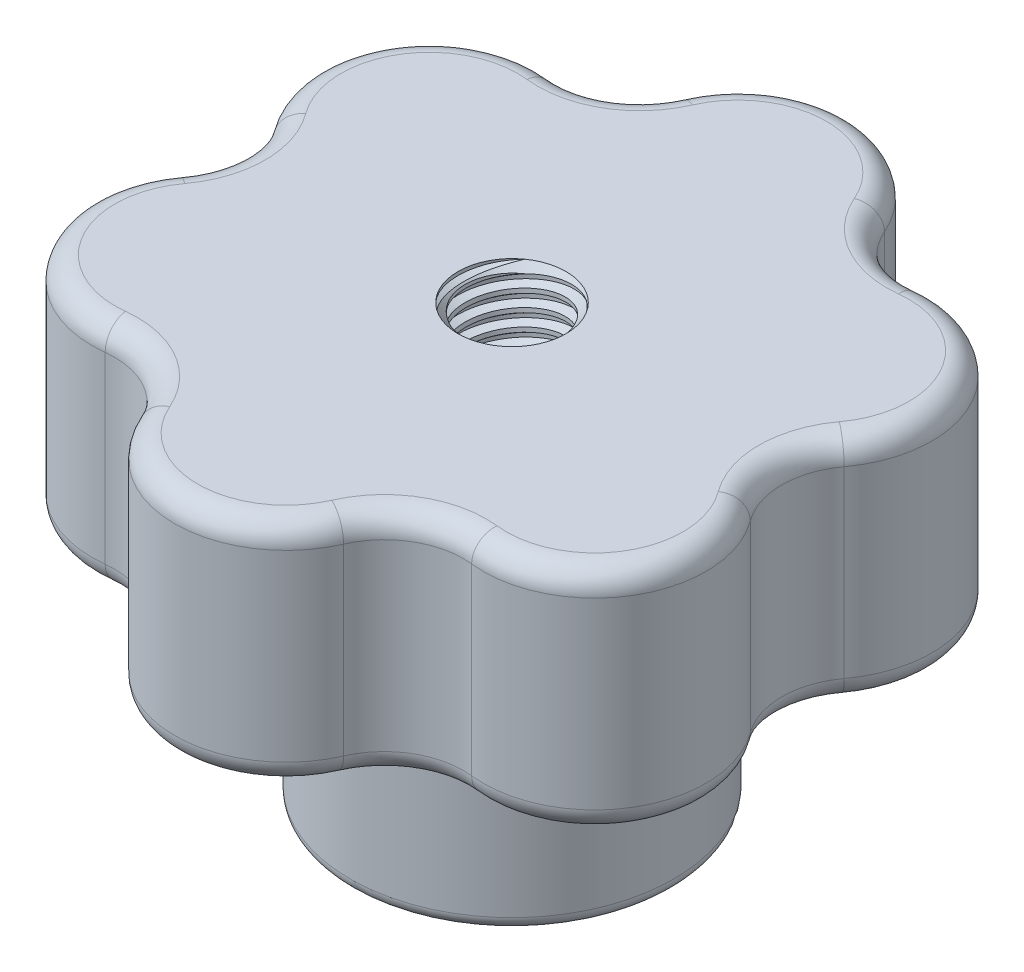
SolidWorks part; units mm, degrees
ref_plane "Front" through (0, 0, 0) normal (0, 0, 1) x (1, 0, 0)
ref_plane "Top" through (0, 0, 0) normal (0, 1, 0) x (1, 0, 0)
ref_plane "Right" through (0, 0, 0) normal (1, 0, 0) x (0, 0, -1)
sketch "Sketch1" plane through (0, 0, 0) normal (0, 0, 1) x (1, 0, 0)
  line L0 (0, 0) -> (12, 0)
  line L1 (12, 0) -> (12, 15)
  line L2 (12, 15) -> (25, 15)
  line L3 (25, 15) -> (25, 32)
  line L4 (0, 44.8994) -> (0, 32) construction
  line L5 (0, 0) -> (0, -12) construction
  line L7 (0, 0) -> (-12, 0) construction
  line L9 (0, 32) -> (25, 32)
  line L10 (0, 32) -> (0, 0)
  dimension "B Base Dia" = 24
  dimension "A OD" = 50
  dimension "F Base Height" = 15
  dimension "D5" = 90
  dimension "D6" = 0
  dimension "D1" = 17
  dimension "D2" = 32
revolve "Revolve1" add sketch "Sketch1" angle 360 about L5
ref_plane "Plane1" through (0, 15, 0) normal (0, 1, 0) x (-1, 0, 0)
sketch "Sketch11" plane through (0, 0, 0) normal (0, 1, 0) x (1, 0, 0)
  line L0 (0, 0) -> (21.6506, -12.5) construction
  line L1 (0, 0) -> (21.6506, 12.5) construction
  line L2 (-20, 0) -> (-25, 0) construction
  line L3 (21.6506, -12.5) -> (24.2487, -14)
  line L4 (21.6506, 12.5) -> (24.2487, 14)
  circle A0 centre (0, 0) radius 20 construction
  arc A1 (21.1438, 3.4759) -> (21.1438, -3.4759) centre (25.8534, 0) ccw
  arc A2 (21.1438, -3.4759) -> (21.6506, -12.5) centre (14.5059, -8.375) cw
  arc A3 (21.1438, 3.4759) -> (21.6506, 12.5) centre (14.5059, 8.375) ccw
  circle A5 centre (0, 0) radius 25 construction
  circle A6 centre (0, 0) radius 28
  arc A7 (24.2487, -14) -> (24.2487, 14) centre (0, 0) ccw
  dimension "D1" = 40
  dimension "D4" = 8.25
  dimension "D3" = 5
  dimension "D5" = 60
  dimension "D2" = 3
extrude "Cut-Extrude2" cut sketch "Sketch11" along normal through all
pattern_circular "CirPattern1" count 6 over 360 about axis through (0, 0, 0) along (0, 1, 0) of "Cut-Extrude2"
sketch "Sketch5" plane through (0, 0, 0) normal (0, 0, 1) x (1, 0, 0)
  line L0 (0, 0) -> (0, -12) construction
  line L1 (0, 0) -> (4, 0)
  line L2 (0, 0) -> (0, 32)
  line L3 (0, 32) -> (4, 32)
  line L4 (4, 0) -> (4, 32)
  line L5 (0, 0) -> (0, -12) construction
  line L7 (-4, 0) -> (-4, 32) construction
  line L8 (7.5617, 32) -> (-7.5617, 32) construction
  dimension "Thread Dia" = 8
revolve "Revolve2" add sketch "Sketch5" angle 360 about L5
sketch "Sketch6" plane through (0, 0, 0) normal (0, 0, 1) x (1, 0, 0)
  line L0 (4, 32) -> (-4, 32) construction
  line L1 (-4, 32) -> (-4, 30.75) construction
  line L2 (-4, 30.75) -> (4, 32) construction
  line L3 (4, 32) -> (4.0241, 31.8456) construction
  line L4 (4.0241, 31.8456) -> (4.193, 30.765)
  line L5 (4.193, 30.765) -> (3.4642, 31.0465)
  line L6 (3.4642, 31.0465) -> (3.416, 31.3552)
  line L7 (3.416, 31.3552) -> (4.0241, 31.8456)
  line L8 (4.1085, 31.3053) -> (3.4401, 31.2009) construction
  line L9 (4, 32) -> (4, 31.2883) construction
  line L10 (4, 31.2883) -> (-4, 30.0383) construction
  line L11 (-4, 30.0383) -> (-4, 30.75) construction
  line L12 (4, 0) -> (4, 32) construction
  line L13 (-4, 0) -> (-4, 32) construction
  line L14 (0, 32) -> (4, 32) construction
  line L15 (-0.2089, 32) -> (0.2089, 29.3267) construction
  point P19 (0, 30.6633)
  dimension "D1" = 0.1562
  dimension "D2" = 0.3125
  dimension "Thread Pitch" = 1.25
  dimension "D4" = 1.25
  dimension "D3" = 60
  dimension "D5" = 32
revolve "Cut-Revolve1" cut sketch "Sketch6" angle 360 about L15
pattern_linear "LPattern1" count 26 spacing 1.25 along (0, -1, 0) count 2 spacing 1.25 along (0, 1, 0) of "Cut-Revolve1"
sketch "Sketch7" plane through (0, 0, 0) normal (0, 0, 1) x (1, 0, 0)
  line L0 (0, 0) -> (4, 0)
  line L1 (4, 0) -> (3.416, 0.584)
  line L2 (7.5617, 32) -> (-7.5617, 32) construction
  line L3 (0, 32) -> (0, 0)
  line L7 (0, 32) -> (4, 32)
  line L8 (0, 16) -> (3.416, 16) construction
  line L9 (0, 0) -> (0, -12) construction
  line L10 (0, 0) -> (0, -12) construction
  line L11 (3.416, 0.584) -> (3.416, 31.416)
  line L12 (4, 32) -> (3.416, 31.416)
  dimension "D1" = 45
revolve "Cut-Revolve2" cut sketch "Sketch7" angle 360 about L10
combine bodies "Combine1" operation type subtract main body 114 bodies to subtract 113
fillet "Fillet1" radius 1.7 24 edges at (20, 15, 0) (21.6506, 15, 12.5) (10, 15, 17.3205) (0, 15, 25) (-10, 15, 17.3205) (-21.6506, 15, 12.5) (-20, 15, 0) (-21.6506, 15, -12.5) (-10, 15, -17.3205) (0, 15, -25) (10, 15, -17.3205) (10, 32, -17.3205) (0, 32, -25) (-10, 32, -17.3205) (-21.6506, 32, -12.5) (-20, 32, 0) (-21.6506, 32, 12.5) (-10, 32, 17.3205) (0, 32, 25) (10, 32, 17.3205) (21.6506, 32, 12.5) (20, 32, 0) (21.6506, 15, -12.5) (21.6506, 32, -12.5)
fillet "Fillet2" radius 1 1 edges at (-12, 0, 0)
sketch "Sketch12" plane through (0, 32, 0) normal (0, 1, 0) x (1, 0, 0)
  circle A0 centre (0, 0) radius 25
  arc A3 (21.1438, 3.4759) -> (13.5821, 16.5731) centre (14.5059, 8.375) ccw construction
equation "\"D1@Sketch6\"=\"Thread Pitch@Sketch6\"/8"
equation "\"D2@Sketch6\"=\"Thread Pitch@Sketch6\"/4"
equation "\"D4@Sketch6\"=\"Thread Pitch@Sketch6\""
equation "\"D4@LPattern1\"=\"Thread Pitch@Sketch6\""
equation "\"D3@LPattern1\"=\"Thread Pitch@Sketch6\""
equation "\"D1@LPattern1\"=\"D2@Sketch1\"/\"Thread Pitch@Sketch6\""
equation "\"D1@Sketch11\" = \"A OD@Sketch1\"*.8"
equation "\"D4@Sketch11\" = \"D3@Sketch11\"*1.65"
equation "\"D1@Fillet1\" = \"D1@Sketch1\"/10"
